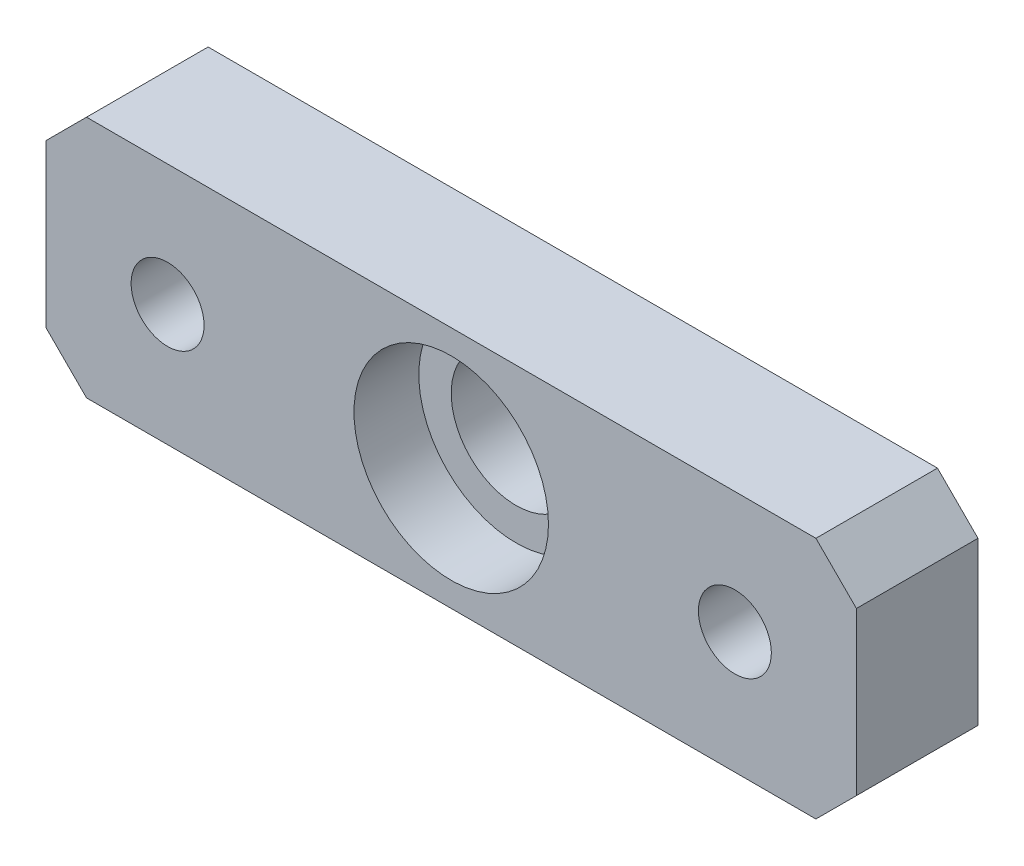
SolidWorks part; units mm, degrees
ref_plane "前视基准面" through (0, 0, 0) normal (0, 0, 1) x (1, 0, 0)
ref_plane "上视基准面" through (0, 0, 0) normal (0, 1, 0) x (1, 0, 0)
ref_plane "右视基准面" through (0, 0, 0) normal (1, 0, 0) x (0, 0, -1)
sketch "草图1" plane through (0, 0, 0) normal (0, 0, 1) x (1, 0, 0)
  line L1 (0, 0) -> (100, 0)
  line L2 (0, 0) -> (0, 30)
  line L3 (0, 30) -> (100, 30)
  line L4 (100, 0) -> (100, 30)
  circle A0 centre (15, 15) radius 4.5
  circle A1 centre (50, 15) radius 8
  circle A2 centre (85, 15) radius 4.5
  dimension "D3" = 9
  dimension "D4" = 9
  dimension "D5" = 15
  dimension "D6" = 35
  dimension "D7" = 35
  dimension "D8" = 15
  dimension "D9" = 15
  dimension "D10" = 15
  dimension "D11" = 16
  dimension "D1" = 100
  dimension "D2" = 30
extrude "凸台-拉伸1" add sketch "草图1" along normal blind 15
sketch "草图2" plane through (0, 0, 15) normal (0, 0, 1) x (1, 0, 0)
  circle A0 centre (50, 15) radius 12
  dimension "D1" = 24
extrude "切除-拉伸1" cut sketch "草图2" against normal blind 8
sketch "草图3" plane through (0, 0, 0) normal (0, 0, -1) x (-1, 0, 0)
  circle A0 centre (-85, 15) radius 6.5
  circle A1 centre (-15, 15) radius 6.5
  dimension "D1" = 13
  dimension "D2" = 13
extrude "切除-拉伸2" cut sketch "草图3" against normal blind 8
chamfer "倒角1" distance 5 angle 45 4 edges at (100, 0, 7.5) (0, 0, 7.5) (0, 30, 7.5) (100, 30, 7.5)
